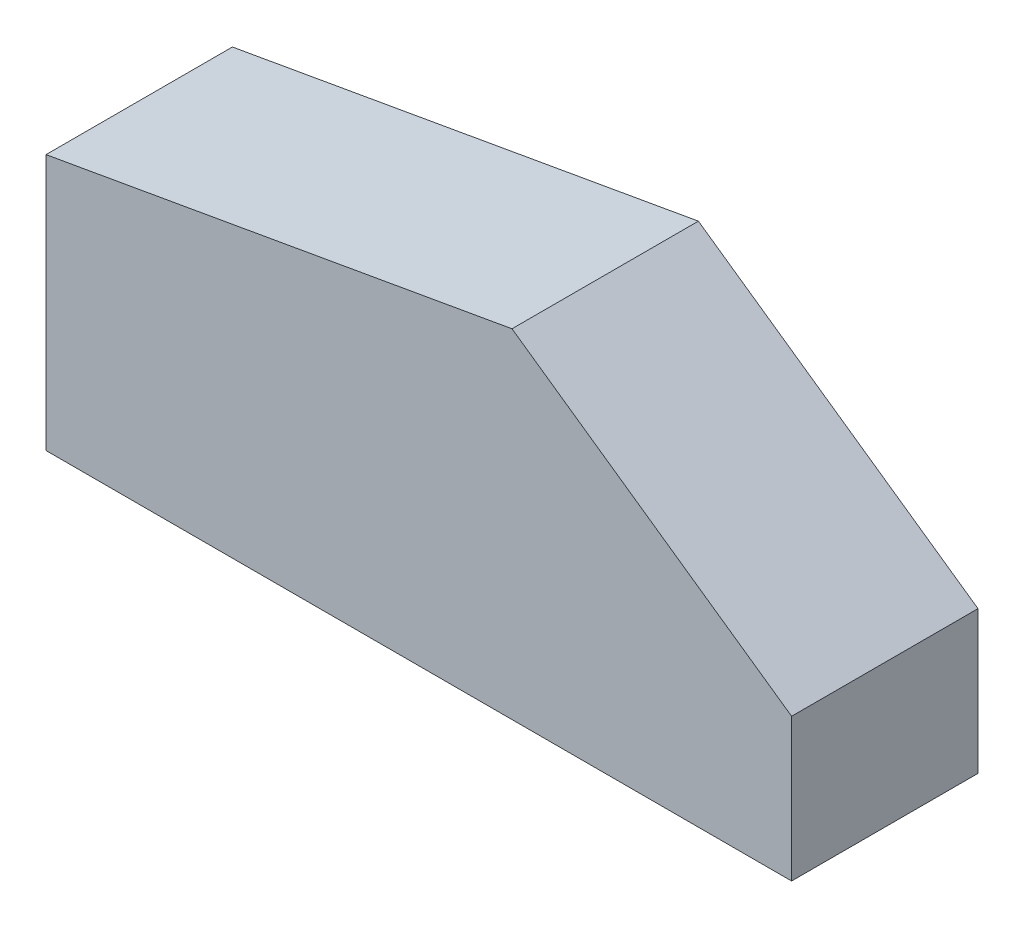
SolidWorks part; units mm, degrees
material "Malleable Cast Iron"
ref_plane "Front Plane" through (0, 0, 0) normal (0, 0, 1) x (1, 0, 0)
ref_plane "Top Plane" through (0, 0, 0) normal (0, 1, 0) x (1, 0, 0)
ref_plane "Right Plane" through (0, 0, 0) normal (1, 0, 0) x (0, 0, -1)
sketch "Sketch1" plane through (0, 0, 0) normal (0, 0, 1) x (1, 0, 0)
  line L0 (0, 0) -> (40, 0)
  line L1 (40, 0) -> (40, 7.6551)
  line L2 (40, 7.6551) -> (25, 18.1582)
  line L3 (25, 18.1582) -> (0, 13.75)
  line L4 (0, 13.75) -> (0, 0)
  dimension "D1" = 100
  dimension "D2" = 135
  dimension "D3" = 40
  dimension "D4" = 13.75
  dimension "D5" = 25
extrude "Boss-Extrude1" add sketch "Sketch1" along normal blind 10
